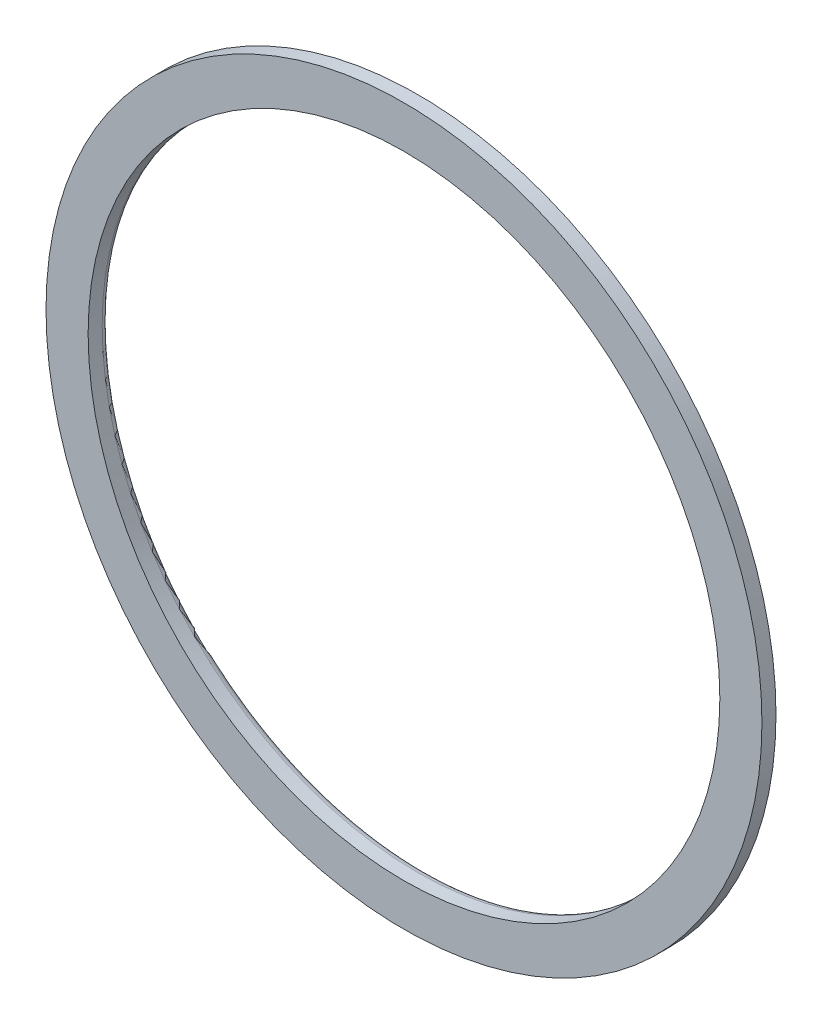
SolidWorks part; units mm, degrees
ref_plane "前视基准面" through (0, 0, 0) normal (0, 0, 1) x (1, 0, 0)
ref_plane "上视基准面" through (0, 0, 0) normal (0, 1, 0) x (1, 0, 0)
ref_plane "右视基准面" through (0, 0, 0) normal (1, 0, 0) x (0, 0, -1)
sketch "草图2" plane through (0, 0, 0) normal (0, 1, 0) x (1, 0, 0)
  line L0 (0, 0) -> (45, 0)
  line L1 (0, 0) -> (0, 5)
  line L2 (45, 0) -> (51, 0)
  line L3 (45, 0) -> (45, 2)
  line L4 (47, 2) -> (51, 2)
  line L5 (51, 0) -> (51, 2)
  arc A0 (47, 2) -> (45, 2) centre (46, 2) ccw
  dimension "D1" = 45
  dimension "D2" = 6
  dimension "D3" = 2
revolve "旋转1" add sketch "草图2" angle 360 about L1
